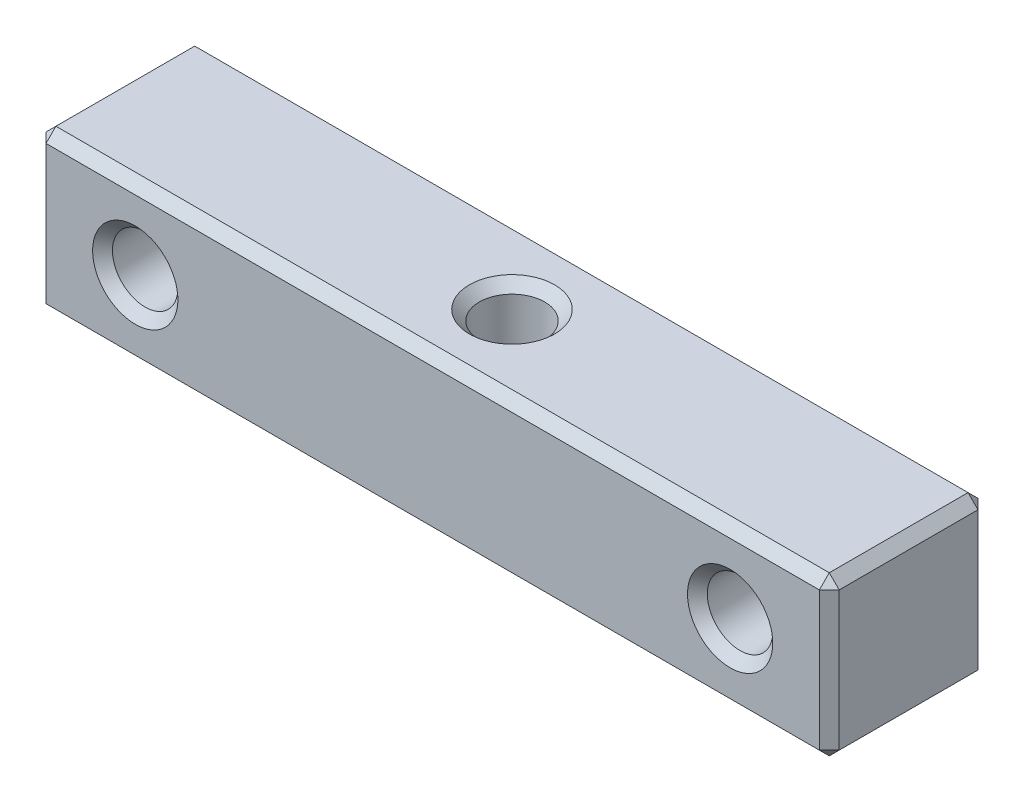
SolidWorks part; units mm, degrees
material "6061 合金"
ref_plane "前视基准面" through (0, 0, 0) normal (0, 0, 1) x (1, 0, 0)
ref_plane "上视基准面" through (0, 0, 0) normal (0, 1, 0) x (1, 0, 0)
ref_plane "右视基准面" through (0, 0, 0) normal (1, 0, 0) x (0, 0, -1)
other "Configuration Table"
sketch "草图1" plane through (0, 0, 0) normal (0, 0, 1) x (1, 0, 0)
  line L0 (-15, 0) -> (15, 0) construction
  line L1 (-20, -4) -> (20, -4)
  line L2 (-20, -4) -> (-20, 4)
  line L3 (-20, 4) -> (20, 4)
  line L4 (20, -4) -> (20, 4)
  line L5 (-20, -4) -> (20, 4) construction
  line L6 (-20, 4) -> (20, -4) construction
  point P0 (0, 0)
  point P9 (0, 0)
  dimension "D1" = 30
  dimension "D2" = 5
  dimension "D3" = 8
extrude "凸台-拉伸1" add sketch "草图1" along normal mid plane 8
sketch "草图2" plane through (0, 0, 4) normal (0, 0, 1) x (1, 0, 0)
  line L0 (-15, 0) -> (15, 0) construction
  point P4 (0, 0)
  dimension "D1" = 30
hole_wizard "M4 螺纹孔1" positions "草图3" profile "草图4" tap size "M4" standard "GB"
sketch "草图3" plane through (0, 0, 4) normal (0, 0, 1) x (1, 0, 0)
  point P0 (-15, 0)
  point P3 (15, 0)
sketch "草图4" plane through (-15, 0, 4) normal (1, 0, 0) x (0, -1, 0)
  line L0 (0, 0) -> (0, 11.0914)
  line L1 (0, 11.0914) -> (1.65, 10.1)
  line L2 (1.65, 10.1) -> (1.65, 0)
  line L5 (1.65, 0) -> (0, 0)
  line L10 (0, 11.0914) -> (-1.65, 10.1) construction
  line L11 (0, -6.35) -> (0, 107.95) construction
  dimension "螺纹孔钻头直径" = 3.3
  dimension "螺纹孔钻头深度" = 10.1
  dimension "导头角度" = 118
cosmetic thread "孔螺蚊线1" parameters "D1"=8, "D2"=4
cosmetic thread "孔螺蚊线2" parameters "D1"=8, "D2"=4
hole_wizard "M4 螺纹孔2" positions "草图5" profile "草图6" tap size "M4" standard "GB"
sketch "草图5" plane through (0, 4, 0) normal (0, 1, 0) x (1, 0, 0)
  point P0 (0, 0)
sketch "草图6" plane through (0, 4, 0) normal (1, 0, 0) x (0, 0, 1)
  line L0 (0, 0) -> (0, 11.0914)
  line L1 (0, 11.0914) -> (1.65, 10.1)
  line L2 (1.65, 10.1) -> (1.65, 0)
  line L5 (1.65, 0) -> (0, 0)
  line L10 (0, 11.0914) -> (-1.65, 10.1) construction
  line L11 (0, -6.35) -> (0, 107.95) construction
  dimension "螺纹孔钻头直径" = 3.3
  dimension "螺纹孔钻头深度" = 10.1
  dimension "导头角度" = 118
cosmetic thread "孔螺蚊线3" parameters "D1"=8, "D2"=4
chamfer "倒角1" distance 0.5 angle 45 18 edges at (0, 4, 4) (20, 4, 0) (-20, 4, 0) (-20, -4, 0) (-20, 0, 4) (0, -4, 4) (20, 0, 4) (20, -4, 0) (0, -4, -4) (-20, 0, -4) (0, 4, -4) (20, 0, -4) (13.35, 0, -4) (16.65, 0, 4) (-16.65, 0, -4) (-13.35, 0, 4) (0, -4, 1.65) (0, 4, 1.65)
